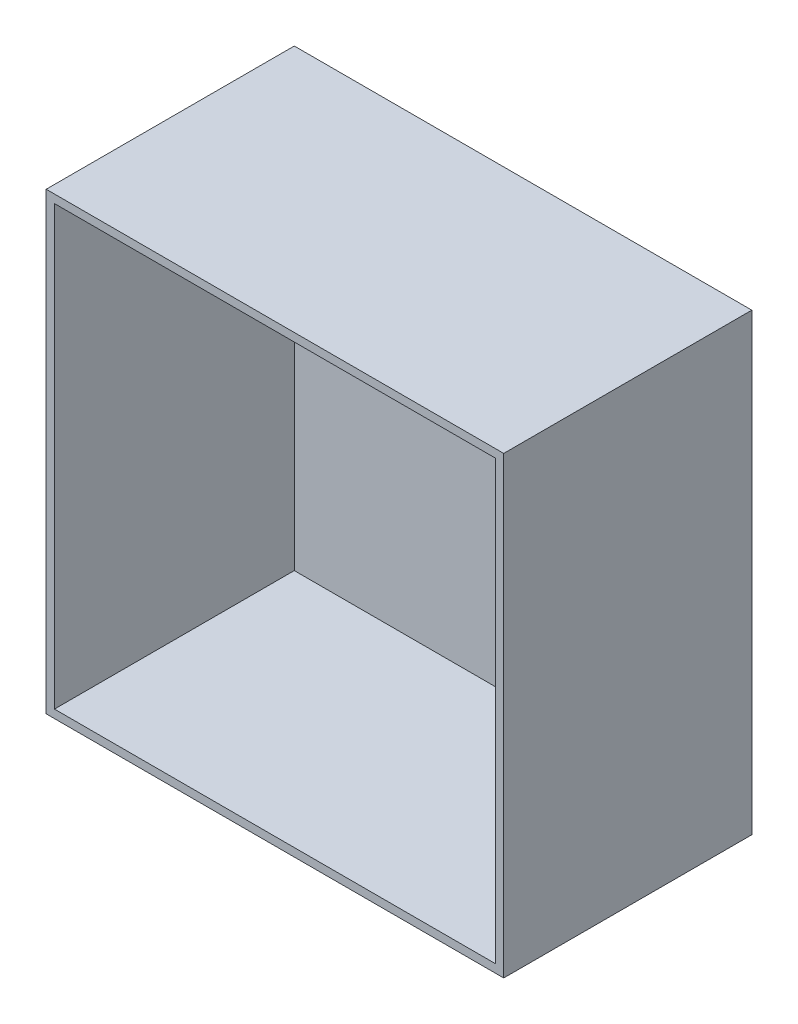
SolidWorks part; units mm, degrees
ref_plane "Přední rovina" through (0, 0, 0) normal (0, 0, 1) x (1, 0, 0)
ref_plane "Horní rovina" through (0, 0, 0) normal (0, 1, 0) x (1, 0, 0)
ref_plane "Pravá rovina" through (0, 0, 0) normal (1, 0, 0) x (0, 0, -1)
sketch "Skica1" plane through (0, 0, 0) normal (0, 0, 1) x (1, 0, 0)
  line L1 (0, 0) -> (-110.835, 0)
  line L2 (0, 0) -> (0, 110.06)
  line L3 (0, 110.06) -> (-110.835, 110.06)
  line L4 (-110.835, 0) -> (-110.835, 110.06)
  dimension "D1" = 110.835
  dimension "D2" = 110.06
extrude "Přidat vysunutím1" add sketch "Skica1" along normal blind 60.1
sketch "Skica2" plane through (0, 0, 60.1) normal (0, 0, 1) x (1, 0, 0)
  line L0 (-55.4175, 110.06) -> (-55.4175, 0) construction
  line L1 (0, 110.06) -> (-110.835, 110.06) construction
  line L2 (-110.835, 0) -> (0, 0) construction
  line L3 (-110.835, 110.06) -> (-110.835, 0) construction
  line L4 (-108.835, 2) -> (-2, 2)
  line L5 (-108.835, 2) -> (-108.835, 108.06)
  line L6 (-108.835, 108.06) -> (-2, 108.06)
  line L7 (-2, 2) -> (-2, 108.06)
  line L8 (-108.835, 2) -> (-2, 108.06) construction
  line L9 (-108.835, 108.06) -> (-2, 2) construction
  point P6 (-55.4175, 55.03)
  dimension "D1" = 2
  dimension "D2" = 2
extrude "Odebrat vysunutím1" cut sketch "Skica2" against normal blind 58.1
